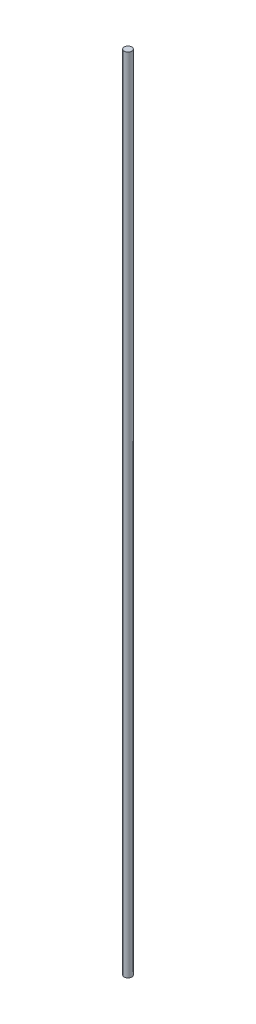
SolidWorks part; units mm, degrees
material "6061-T6 (SS)"
ref_plane "Front Plane" through (0, 0, 0) normal (0, 0, 1) x (1, 0, 0)
ref_plane "Top Plane" through (0, 0, 0) normal (0, 1, 0) x (1, 0, 0)
ref_plane "Right Plane" through (0, 0, 0) normal (1, 0, 0) x (0, 0, -1)
sketch "Sketch1" plane through (0, 0, 0) normal (0, 1, 0) x (1, 0, 0)
  circle A0 centre (0, 0) radius 1
  dimension "D1" = 2
extrude "Boss-Extrude1" add sketch "Sketch1" along normal blind 213.8
